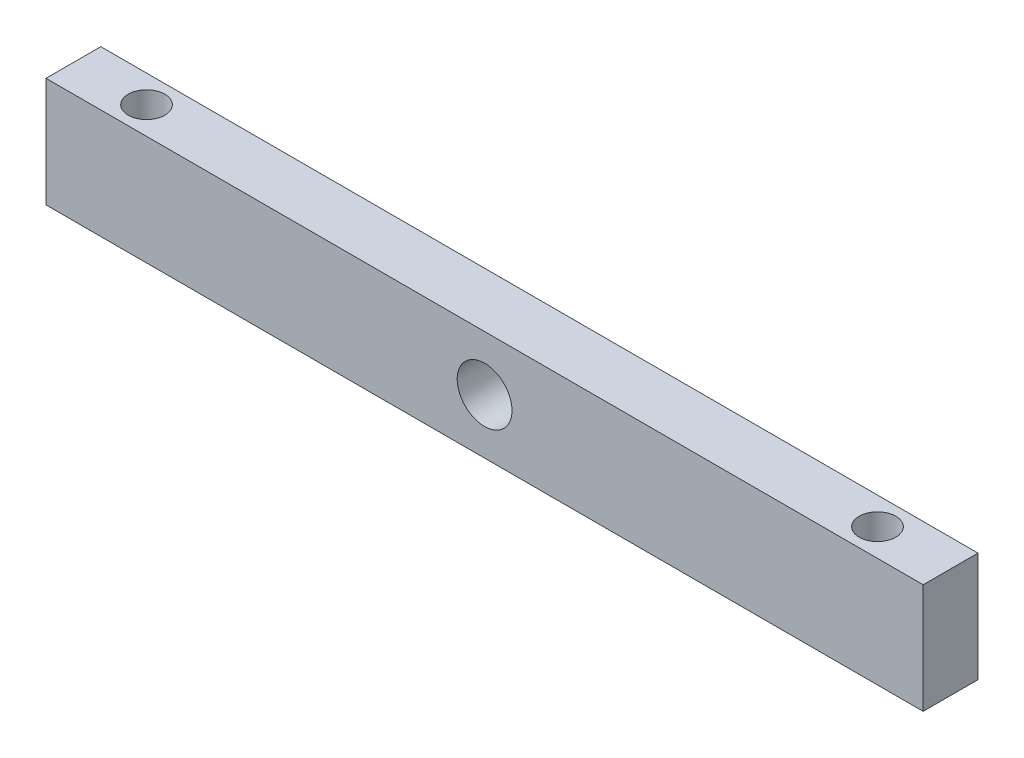
SolidWorks part; units mm, degrees
ref_plane "Plano frontal" through (0, 0, 0) normal (0, 0, 1) x (1, 0, 0)
ref_plane "Plano superior" through (0, 0, 0) normal (0, 1, 0) x (1, 0, 0)
ref_plane "Plano direito" through (0, 0, 0) normal (1, 0, 0) x (0, 0, -1)
sketch "Esboço1" plane through (0, 0, 0) normal (0, 0, 1) x (1, 0, 0)
  line L0 (100, 0) -> (-100, 0)
  line L2 (-100, 30) -> (100, 30)
  line L3 (-100, 30) -> (-120, 30)
  line L4 (-120, 30) -> (-120, 0)
  line L5 (-120, 0) -> (-100, 0)
  line L6 (100, 30) -> (120, 30)
  line L7 (120, 30) -> (120, 0)
  line L8 (100, 0) -> (120, 0)
  point P4 (0, 0)
  dimension "D1" = 30
  dimension "D2" = 20
  dimension "D3" = 20
extrude "Ressalto-extrusão1" add sketch "Esboço1" along normal blind 15
sketch "Esboço2" plane through (0, 0, 15) normal (0, 0, 1) x (1, 0, 0)
  line L0 (0, 30) -> (0, 0)
  line L1 (120, 30) -> (-120, 30) construction
  circle A0 centre (0, 15) radius 7.5
  dimension "D1" = 15
extrude "Corte-extrusão1" cut sketch "Esboço2" against normal blind 15 contours L0 A0 | L0 A0
sketch "Esboço10" plane through (0, 0, 0) normal (0, -1, 0) x (-1, 0, 0)
  line L0 (120, -7.5) -> (100, -7.5)
  line L1 (120, -15) -> (120, 0) construction
  circle A0 centre (100, -7.5) radius 5
  circle A1 centre (-100, -7.5) radius 5
  dimension "D2" = 10
  dimension "D4" = 10
  dimension "D1" = 20
extrude "Corte-extrusão9" cut sketch "Esboço10" against normal blind 79
